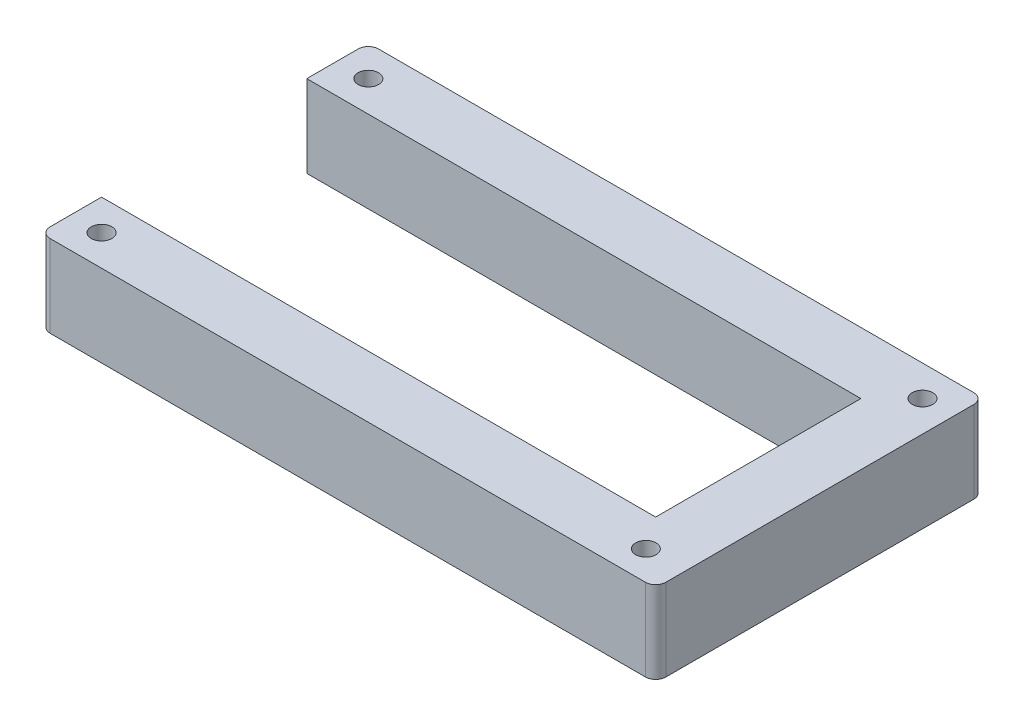
SolidWorks part; units mm, degrees
ref_plane "Front Plane" through (0, 0, 0) normal (0, 0, 1) x (1, 0, 0)
ref_plane "Top Plane" through (0, 0, 0) normal (0, 1, 0) x (1, 0, 0)
ref_plane "Right Plane" through (0, 0, 0) normal (1, 0, 0) x (0, 0, -1)
sketch "Sketch1" plane through (0, 0, 0) normal (0, 1, 0) x (1, 0, 0)
  line L0 (63.5, 0) -> (3746.5, 0)
  line L1 (3810, 63.5) -> (3810, 1968.5)
  line L2 (3746.5, 2032) -> (63.5, 2032)
  line L3 (0, 1968.5) -> (0, 1651)
  line L4 (0, 1651) -> (3429, 1651)
  line L5 (3429, 1651) -> (3429, 381)
  line L6 (3429, 381) -> (0, 381)
  line L7 (0, 381) -> (0, 63.5)
  circle A0 centre (190.5, 1841.5) radius 63.5
  circle A1 centre (190.5, 190.5) radius 63.5
  circle A2 centre (3568.7396, 180.493) radius 63.5
  circle A3 centre (3619.5, 1841.5) radius 63.5
  arc A4 (63.5, 0) -> (0, 63.5) centre (63.5, 63.5) cw
  arc A5 (3746.5, 0) -> (3810, 63.5) centre (3746.5, 63.5) ccw
  arc A6 (3810, 1968.5) -> (3746.5, 2032) centre (3746.5, 1968.5) ccw
  arc A7 (63.5, 2032) -> (0, 1968.5) centre (63.5, 1968.5) ccw
  point P19 (0, 0)
  point P24 (3810, 2032)
  point P27 (0, 2032)
  dimension "D7" = 127
  dimension "D11" = 63.5
  dimension "D1" = 2032
  dimension "D2" = 1270
  dimension "D3" = 381
  dimension "D4" = 3810
  dimension "D5" = 3429
  dimension "D6" = 3429
  dimension "D8" = 1651
  dimension "D9" = 190.5
  dimension "D10" = 190.5
extrude "Boss-Extrude1" add sketch "Sketch1" along normal blind 508
